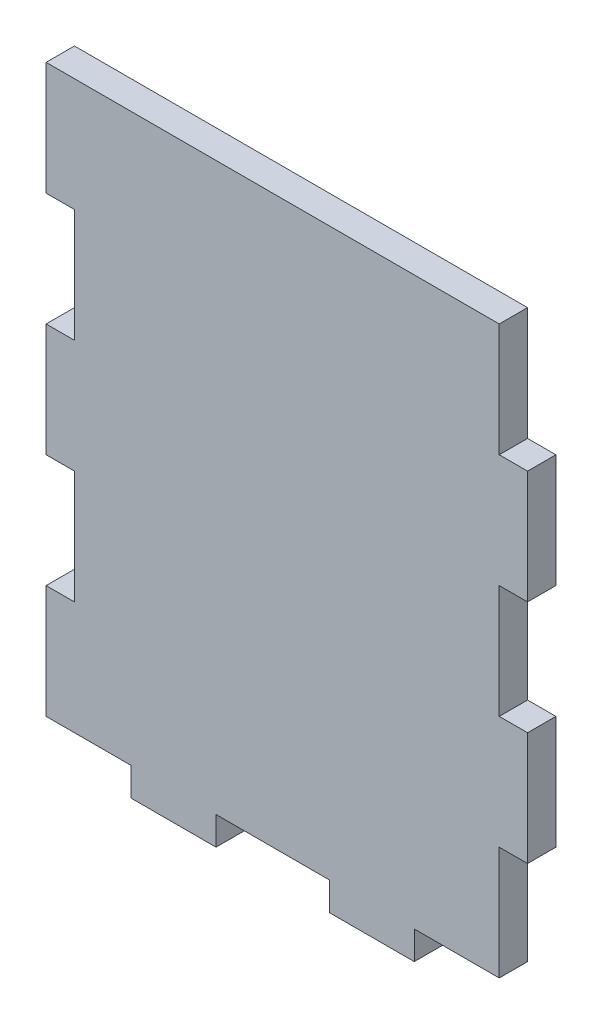
SolidWorks part; units mm, degrees
ref_plane "Front" through (0, 0, 0) normal (0, 0, 1) x (1, 0, 0)
ref_plane "Top" through (0, 0, 0) normal (0, 1, 0) x (1, 0, 0)
ref_plane "Right" through (0, 0, 0) normal (1, 0, 0) x (0, 0, -1)
sketch "Sketch1" plane through (0, 0, 0) normal (0, 0, 1) x (1, 0, 0)
  line L0 (-50.8, 38.1) -> (-50.8, 63.5)
  line L1 (-50.8, -63.5) -> (-31.75, -63.5)
  line L2 (-50.8, -63.5) -> (-50.8, -38.1)
  line L3 (-50.8, 63.5) -> (50.8, 63.5)
  line L4 (50.8, -63.5) -> (50.8, -38.1)
  line L5 (-50.8, -63.5) -> (50.8, 63.5) construction
  line L6 (-50.8, 63.5) -> (50.8, -63.5) construction
  line L7 (-50.8, 38.1) -> (-44.45, 38.1)
  line L8 (-50.8, -12.7) -> (-50.8, 12.7)
  line L9 (-50.8, 12.7) -> (-44.45, 12.7)
  line L10 (-44.45, 38.1) -> (-44.45, 12.7)
  line L11 (-50.8, -12.7) -> (-44.45, -12.7)
  line L12 (50.8, 38.1) -> (50.8, 63.5)
  line L13 (-50.8, -38.1) -> (-44.45, -38.1)
  line L14 (-44.45, -12.7) -> (-44.45, -38.1)
  line L15 (50.8, 38.1) -> (57.15, 38.1)
  line L16 (50.8, -12.7) -> (50.8, 12.7)
  line L17 (50.8, 12.7) -> (57.15, 12.7)
  line L18 (57.15, 38.1) -> (57.15, 12.7)
  line L19 (50.8, -12.7) -> (57.15, -12.7)
  line L20 (-12.7, -63.5) -> (12.7, -63.5)
  line L21 (50.8, -38.1) -> (57.15, -38.1)
  line L22 (57.15, -12.7) -> (57.15, -38.1)
  line L23 (31.75, -63.5) -> (50.8, -63.5)
  line L24 (-31.75, -63.5) -> (-31.75, -69.85)
  line L25 (-31.75, -69.85) -> (-12.7, -69.85)
  line L26 (-12.7, -63.5) -> (-12.7, -69.85)
  line L28 (12.7, -63.5) -> (12.7, -69.85)
  line L29 (12.7, -69.85) -> (31.75, -69.85)
  line L30 (31.75, -63.5) -> (31.75, -69.85)
  point P0 (0, 0)
  dimension "D1" = 127
  dimension "D2" = 101.6
  dimension "D3" = 6.35
  dimension "D4" = 25.4
  dimension "D5" = 25.4
  dimension "D6" = 25.4
  dimension "D7" = 6.35
  dimension "D8" = 19.05
  dimension "D9" = 19.05
  dimension "D10" = 19.05
extrude "BOXSIDE" add sketch "Sketch1" along normal blind 6.35 contours L3 L12 L15 L18 L17 L16 L19 L22 L21 L4 L23 L30 L29 L28 L20 L26 L25 L24 L1 L2 L13 L14 L11 L8 L9 L10 L7 L0
